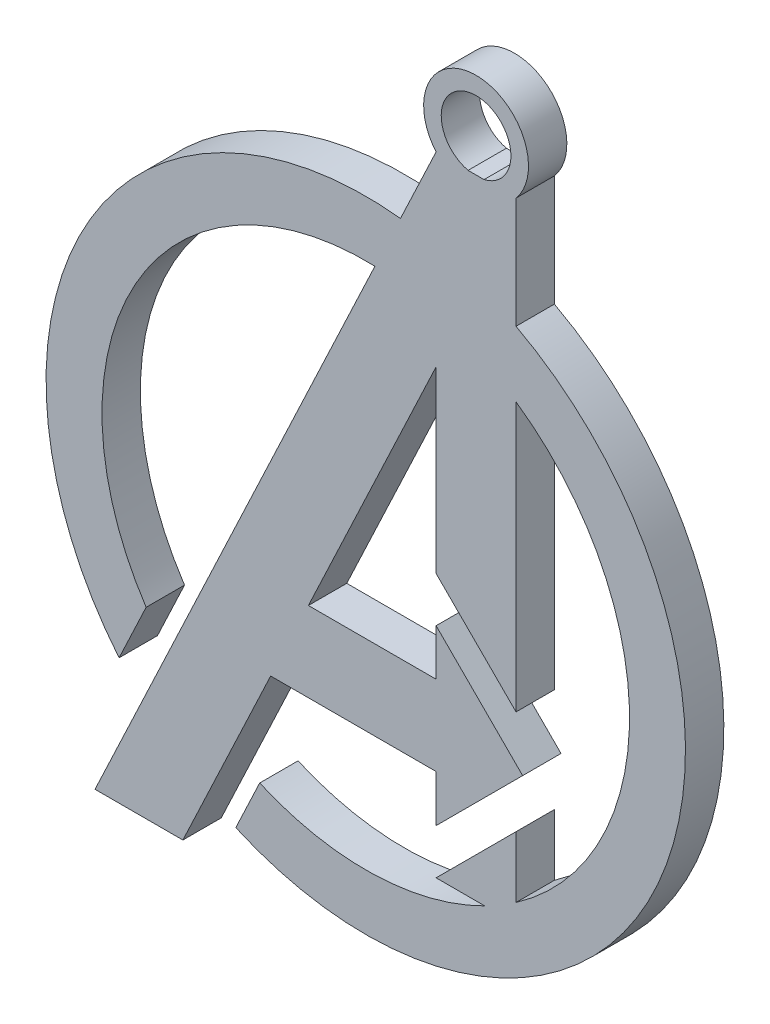
SolidWorks part; units mm, degrees
ref_plane "Front Plane" through (0, 0, 0) normal (0, 0, 1) x (1, 0, 0)
ref_plane "Top Plane" through (0, 0, 0) normal (0, 1, 0) x (1, 0, 0)
ref_plane "Right Plane" through (0, 0, 0) normal (1, 0, 0) x (0, 0, -1)
sketch "Sketch2" plane through (0, 0, 0) normal (0, 0, 1) x (1, 0, 0)
  circle A0 centre (0, 0) radius 25.4
  circle A1 centre (0, 0) radius 20.955
  dimension "D1" = 50.8
  dimension "D2" = 41.91
extrude "Boss-Extrude1" add sketch "Sketch2" along normal blind 3.048 contours A1 | A0
sketch "Sketch3" plane through (0, 0, 0) normal (0, 0, 1) x (1, 0, 0)
  line L1 (5.588, 31.242) -> (11.938, 31.242)
  line L2 (5.588, 31.242) -> (5.588, -18.7028)
  line L3 (5.588, -18.7028) -> (11.938, -18.7028)
  line L4 (11.938, 31.242) -> (11.938, -18.7028)
  dimension "D1" = 31.242
  dimension "D2" = 5.588
  dimension "D3" = 6.35
  dimension "D4" = 49.9448
extrude "Boss-Extrude2" add sketch "Sketch3" along normal blind 3.048
sketch "Sketch6" plane through (0, 0, 0) normal (0, 0, 1) x (1, 0, 0)
  line L0 (0, -26.162) -> (-27.1753, -26.162)
  line L1 (0, -26.162) -> (0, -30.314)
  line L2 (-27.1753, -26.162) -> (-27.1753, -30.314)
  line L3 (0, -30.314) -> (-27.1753, -30.314)
  dimension "D1" = 26.162
  dimension "D2" = 4.152
  dimension "D3" = 27.1753
  dimension "D4" = 27.1753
sketch "Sketch7" plane through (0, 0, 0) normal (0, 0, 1) x (1, 0, 0)
  line L0 (5.588, 31.242) -> (-21.5102, -26.162)
  line L2 (5.588, 31.242) -> (11.2969, 28.547)
  line L3 (-21.5102, -26.162) -> (-15.8013, -28.857)
  line L4 (11.2969, 28.547) -> (-15.8013, -28.857)
  line L5 (0, -26.162) -> (-27.1753, -26.162) construction
  point P3 (-21.5102, -26.162)
  point P8 (0, 0)
  point P9 (-21.5102, -26.162)
  point P10 (-21.5102, -26.162)
  dimension "D1" = 6.3131
  dimension "D2" = 63.4786
sketch "Sketch8" plane through (0, 0, 0) normal (0, 0, 1) x (1, 0, 0)
  line L0 (-11.8823, 0.1836) -> (-24.319, -26.162)
  line L1 (-11.8823, 0.1836) -> (-1.5794, -4.6799)
  line L2 (-24.319, -26.162) -> (-14.0162, -31.0256)
  line L3 (-1.5794, -4.6799) -> (-14.0162, -31.0256)
  line L4 (0, -26.162) -> (-27.1753, -26.162) construction
  line L5 (5.588, 31.242) -> (-21.5102, -26.162) construction
  line L6 (-21.5102, -26.162) -> (-15.8013, -28.857) construction
  line L7 (11.2969, 28.547) -> (-15.8013, -28.857) construction
  dimension "D1" = 29.1336
  dimension "D2" = 2.54
  dimension "D3" = 2.54
extrude "Cut-Extrude1" cut sketch "Sketch8" along normal blind 3.302 contours L0 L1 L3 L2
extrude "Boss-Extrude3" add sketch "Sketch7" along normal blind 3.048
sketch "Sketch9" plane through (0, 0, 0) normal (0, 0, 1) x (1, 0, 0)
  line L0 (5.588, -18.7028) -> (5.588, 2.2364)
  line L1 (5.588, 16.4534) -> (5.588, -18.7028) construction
  line L2 (5.588, 2.2364) -> (16.0576, -8.2332)
  line L3 (16.0576, -8.2332) -> (5.588, -18.7028)
  dimension "D1" = 10.4696
  dimension "D2" = 10.4696
extrude "Cut-Extrude2" cut sketch "Sketch9" along normal blind 3.048 contours L3 L0 L2
sketch "Sketch12" plane through (0, 0, 0) normal (0, 0, 1) x (1, 0, 0)
  line L0 (5.588, -1.3557) -> (12.4655, -8.2332)
  line L1 (5.588, -18.7028) -> (5.588, 2.2364) construction
  line L2 (12.4655, -8.2332) -> (5.588, -15.1107)
  line L3 (5.588, -15.1107) -> (5.588, -1.3557)
  line L4 (5.588, 2.2364) -> (16.0576, -8.2332) construction
  line L5 (16.0576, -8.2332) -> (5.588, -18.7028) construction
  line L6 (-15.8013, -28.857) -> (5.588, 16.4534) construction
  line L7 (5.588, -5.0387) -> (-7.5552, -5.0387)
  line L8 (5.588, -5.0387) -> (5.588, -11.3887)
  line L9 (5.588, -11.3887) -> (-7.5552, -11.3887)
  line L10 (-7.5552, -5.0387) -> (-7.5552, -11.3887)
  point P15 (0, 0)
  point P16 (0, 0)
  point P17 (0, 0)
  point P18 (0, 0)
  dimension "D1" = 2.54
  dimension "D2" = 2.54
  dimension "D3" = 6.35
  dimension "D4" = 13.755
  dimension "D5" = 3.683
extrude "Boss-Extrude5" add sketch "Sketch12" along normal blind 3.048 contours L3 L2 L0 | L8 L7 L10 L9
extrude "Cut-Extrude4" cut sketch "Sketch6" along normal blind 3.048
sketch "Sketch13" plane through (0, 0, 0) normal (0, 0, 1) x (1, 0, 0)
  line L0 (11.938, 31.242) -> (5.588, 31.242) construction
  line L1 (5.588, 31.242) -> (8.128, 31.242)
  line L3 (9.398, 31.242) -> (11.938, 31.242)
  arc A0 (5.588, 31.242) -> (11.938, 31.242) centre (8.763, 33.9375) cw
  arc A1 (8.128, 31.242) -> (9.398, 31.242) centre (8.763, 33.9375) cw
  dimension "D1" = 2.54
  dimension "D3" = 0
  dimension "D2" = 1.3956
  dimension "D4" = 2.6955
extrude "Boss-Extrude6" add sketch "Sketch13" along normal blind 3.048
